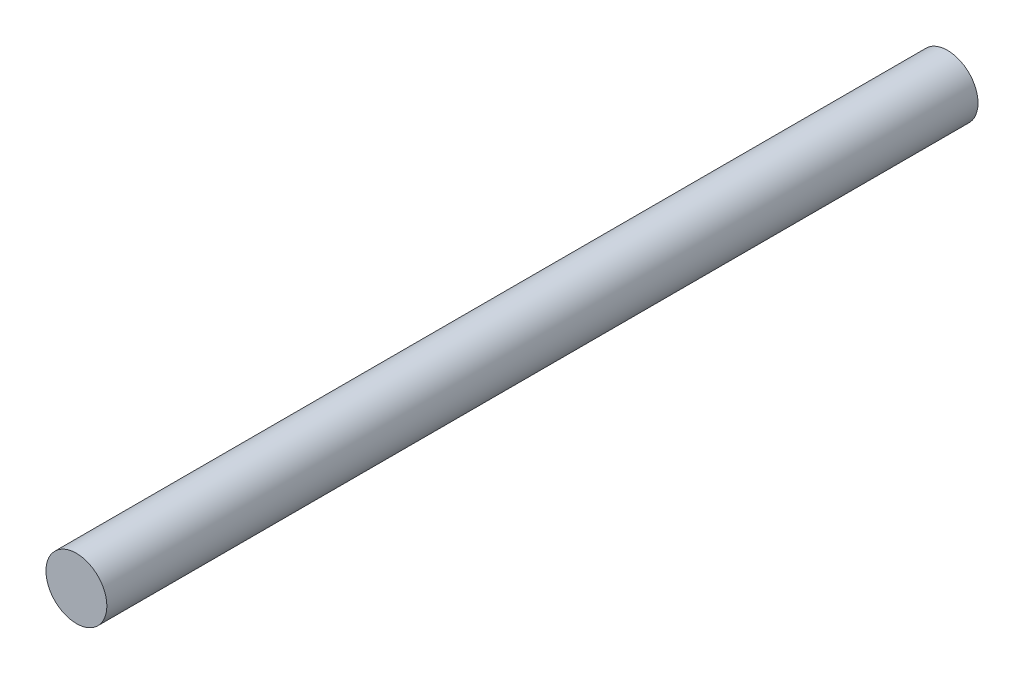
SolidWorks part; units mm, degrees
ref_plane "Front Plane" through (0, 0, 0) normal (0, 0, 1) x (1, 0, 0)
ref_plane "Top Plane" through (0, 0, 0) normal (0, 1, 0) x (1, 0, 0)
ref_plane "Right Plane" through (0, 0, 0) normal (1, 0, 0) x (0, 0, -1)
sketch "Sketch1" plane through (0, 0, 0) normal (0, 0, 1) x (1, 0, 0)
  circle A0 centre (0, 0) radius 4
  dimension "D1" = 8
extrude "Boss-Extrude1" add sketch "Sketch1" along normal blind 114.4
